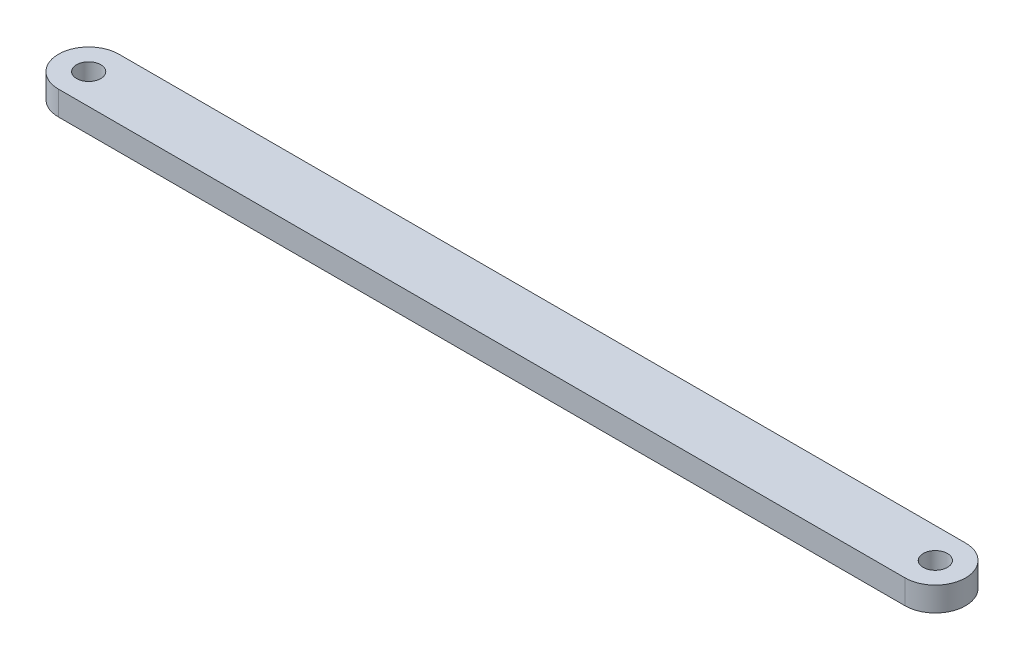
SolidWorks part; units mm, degrees
ref_plane "Front Plane" through (0, 0, 0) normal (0, 0, 1) x (1, 0, 0)
ref_plane "Top Plane" through (0, 0, 0) normal (0, 1, 0) x (1, 0, 0)
ref_plane "Right Plane" through (0, 0, 0) normal (1, 0, 0) x (0, 0, -1)
sketch "Sketch1" plane through (0, 0, 0) normal (0, 1, 0) x (1, 0, 0)
  line L0 (-10, 0) -> (60, 0) construction
  line L1 (-10, 2.5) -> (60, 2.5)
  line L2 (-10, -2.5) -> (60, -2.5)
  arc A0 (-10, 2.5) -> (-10, -2.5) centre (-10, 0) ccw
  arc A1 (60, -2.5) -> (60, 2.5) centre (60, 0) ccw
  circle A2 centre (60, 0) radius 1
  circle A3 centre (-10, 0) radius 1
  point P3 (25, 0)
  dimension "D3" = 2
  dimension "D4" = 2.5
  dimension "D5" = 2
  dimension "D1" = 70
  dimension "D12" = 10
extrude "Boss-Extrude1" add sketch "Sketch1" along normal blind 2
